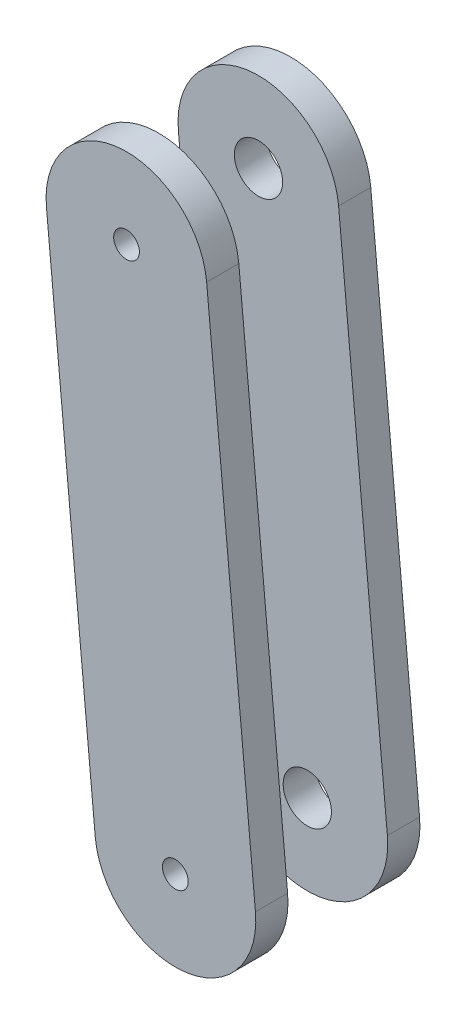
SolidWorks part; units mm, degrees
material "ABS"
ref_plane "正面" through (0, 0, 0) normal (0, 0, 1) x (1, 0, 0)
ref_plane "平面" through (0, 0, 0) normal (0, 1, 0) x (1, 0, 0)
ref_plane "右側面" through (0, 0, 0) normal (1, 0, 0) x (0, 0, -1)
sketch "ｽｹｯﾁ1" plane through (0, 0, 0) normal (0, 0, 1) x (1, 0, 0)
  line L0 (0, 60) -> (0, 0) construction
  line L1 (0, 0) -> (-30, 0) construction
  line L2 (-30, 0) -> (-36.0667, 64.7398) construction
  line L3 (-36.0667, 64.7398) -> (-80, 55) construction
  line L4 (-80, 55) -> (-90.7898, 55) construction
  line L5 (-36.0667, 64.7398) -> (-36.0667, -26) construction
  line L6 (-36.0667, 64.7398) -> (-30, 0) construction
  line L7 (-26.1103, 65.6728) -> (-20.0436, 0.933)
  line L8 (-46.0231, 63.8068) -> (-39.9564, -0.933)
  circle A0 centre (-36.0667, 64.7398) radius 1.6
  circle A1 centre (-30, 0) radius 1.6
  arc A2 (-26.1103, 65.6728) -> (-46.0231, 63.8068) centre (-36.0667, 64.7398) ccw
  arc A3 (-39.9564, -0.933) -> (-20.0436, 0.933) centre (-30, 0) ccw
  point P10 (-33.0333, 32.3699)
  dimension "D7" = 3.2
  dimension "D8" = 10
  dimension "D1" = 5
  dimension "D2" = 80
  dimension "D3" = 60
  dimension "D4" = 30
  dimension "D5" = 12.5
  dimension "D6" = 45
extrude "ﾎﾞｽ - 押し出し1" add sketch "ｽｹｯﾁ1" along normal blind 4
ref_plane "平面1" through (0, 0, -12.4) normal (0, 0, -1) x (-1, 0, 0)
sketch "ｽｹｯﾁ3" plane through (0, 0, -12.4) normal (0, 0, -1) x (-1, 0, 0)
  line L2 (26.1103, 65.6728) -> (20.0436, 0.933)
  line L3 (39.9564, -0.933) -> (46.0231, 63.8068)
  line L4 (26.1103, 65.6728) -> (20.0436, 0.933)
  line L5 (39.9564, -0.933) -> (46.0231, 63.8068)
  circle A0 centre (30, 0) radius 3
  circle A1 centre (36.0667, 64.7398) radius 3
  arc A2 (46.0231, 63.8068) -> (26.1103, 65.6728) centre (36.0667, 64.7398) ccw
  arc A3 (20.0436, 0.933) -> (39.9564, -0.933) centre (30, 0) ccw
  arc A4 (46.0231, 63.8068) -> (26.1103, 65.6728) centre (36.0667, 64.7398) ccw
  arc A5 (20.0436, 0.933) -> (39.9564, -0.933) centre (30, 0) ccw
  dimension "D2" = 6
  dimension "D3" = 6
  dimension "D1" = 0
extrude "ﾎﾞｽ - 押し出し2" add sketch "ｽｹｯﾁ3" along normal blind 4 separate body
